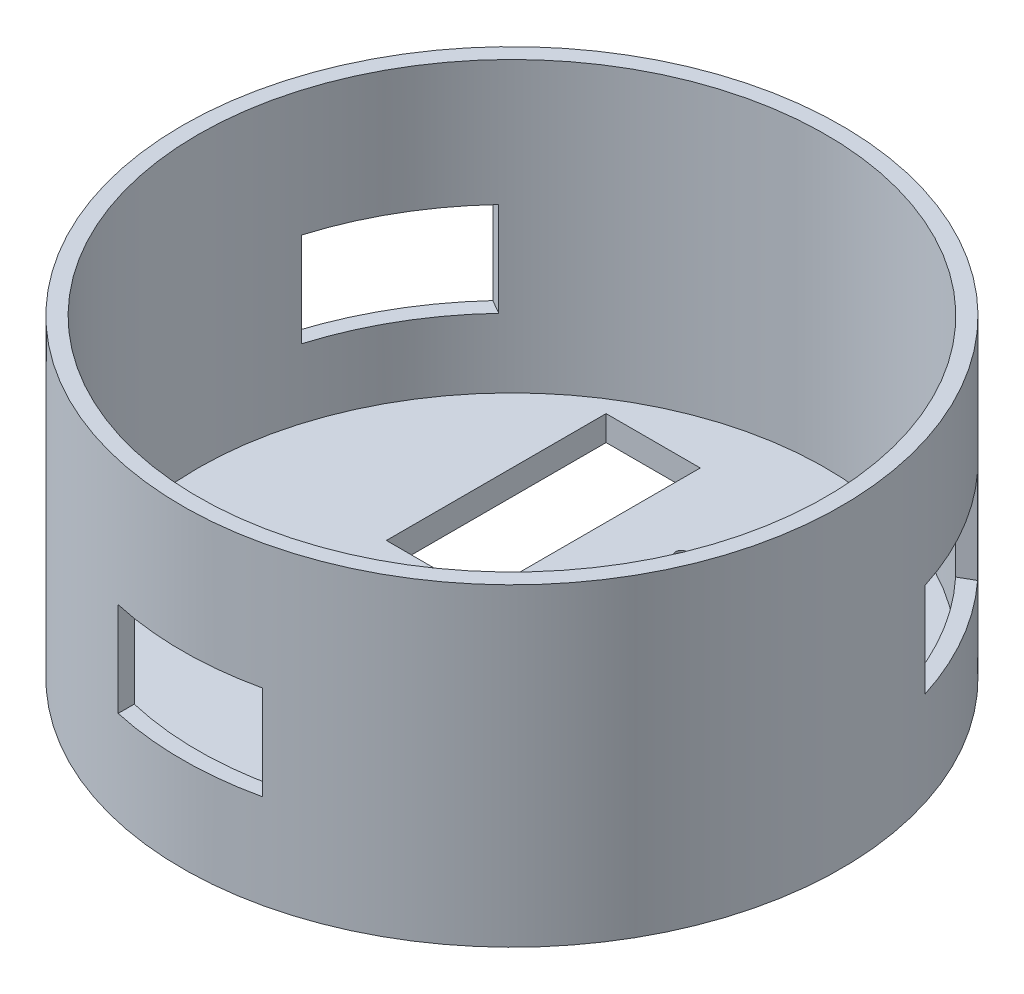
SolidWorks part; units mm, degrees
ref_plane "前视基准面" through (0, 0, 0) normal (0, 0, 1) x (1, 0, 0)
ref_plane "上视基准面" through (0, 0, 0) normal (0, 1, 0) x (1, 0, 0)
ref_plane "右视基准面" through (0, 0, 0) normal (1, 0, 0) x (0, 0, -1)
other "Configuration Table"
sketch "草图1" plane through (0, 0, 0) normal (0, 0, 1) x (1, 0, 0)
  line L1 (0, 100) -> (0, 0) construction
  line L2 (0, 0) -> (0, 100) construction
  line L8 (-105, 100) -> (-100, 100)
  line L9 (-105, 100) -> (-105, 0)
  line L12 (-100, 8) -> (0, 8)
  line L13 (0, 8) -> (0, 0)
  line L14 (-100, 100) -> (-100, 8)
  line L15 (-105, 0) -> (0, 0)
  dimension "D1" = 100
  dimension "D2" = 100
  dimension "D3" = 5
  dimension "D4" = 105
  dimension "D6" = 8
revolve "旋转1" add sketch "草图1" angle 360 about L1
sketch "草图2" plane through (0, 0, 0) normal (0, 0, 1) x (1, 0, 0)
  line L1 (-23, 60) -> (23, 60)
  line L2 (-23, 60) -> (-23, 30)
  line L3 (-23, 30) -> (23, 30)
  line L4 (23, 60) -> (23, 30)
  line L5 (-23, 60) -> (23, 30) construction
  line L6 (-23, 30) -> (23, 60) construction
  line L8 (0, 45) -> (0, 0) construction
  point P0 (0, 45)
  dimension "D1" = 46
  dimension "D2" = 30
  dimension "D3" = 30
  dimension "D4" = 45
extrude "切除-拉伸1" cut sketch "草图2" along normal through all
pattern_circular "阵列(圆周)1" count 3 every 120 about axis through (0, 0, 0) along (0, 1, 0) of "切除-拉伸1"
sketch "草图3" plane through (0, 0, 0) normal (0, 1, 0) x (1, 0, 0)
  line L0 (20, -80) -> (50, -80)
  line L1 (20, -10) -> (20, -80)
  line L2 (50, -10) -> (20, -10)
  line L3 (50, -80) -> (50, -10)
  line L4 (-17, -54.8) -> (-1, -54.8)
  line L5 (-1, -51.2) -> (-17, -51.2)
  line L6 (-17, -38.8) -> (-1, -38.8)
  line L7 (-1, -35.2) -> (-17, -35.2)
  line L8 (17, 38.8) -> (1, 38.8)
  line L9 (1, 35.2) -> (17, 35.2)
  line L10 (17, 54.8) -> (1, 54.8)
  line L11 (1, 51.2) -> (17, 51.2)
  line L12 (-20, 80) -> (-50, 80)
  line L13 (-20, 10) -> (-20, 80)
  line L14 (-50, 10) -> (-20, 10)
  line L15 (-50, 80) -> (-50, 10)
  arc A0 (-17, -51.2) -> (-17, -54.8) centre (-17, -53) ccw
  arc A1 (-1, -54.8) -> (-1, -51.2) centre (-1, -53) ccw
  arc A2 (-17, -35.2) -> (-17, -38.8) centre (-17, -37) ccw
  arc A3 (-1, -38.8) -> (-1, -35.2) centre (-1, -37) ccw
  arc A4 (17, 35.2) -> (17, 38.8) centre (17, 37) ccw
  arc A5 (1, 38.8) -> (1, 35.2) centre (1, 37) ccw
  arc A6 (17, 51.2) -> (17, 54.8) centre (17, 53) ccw
  arc A7 (1, 54.8) -> (1, 51.2) centre (1, 53) ccw
extrude "切除-拉伸2" cut sketch "草图3" along normal through all
